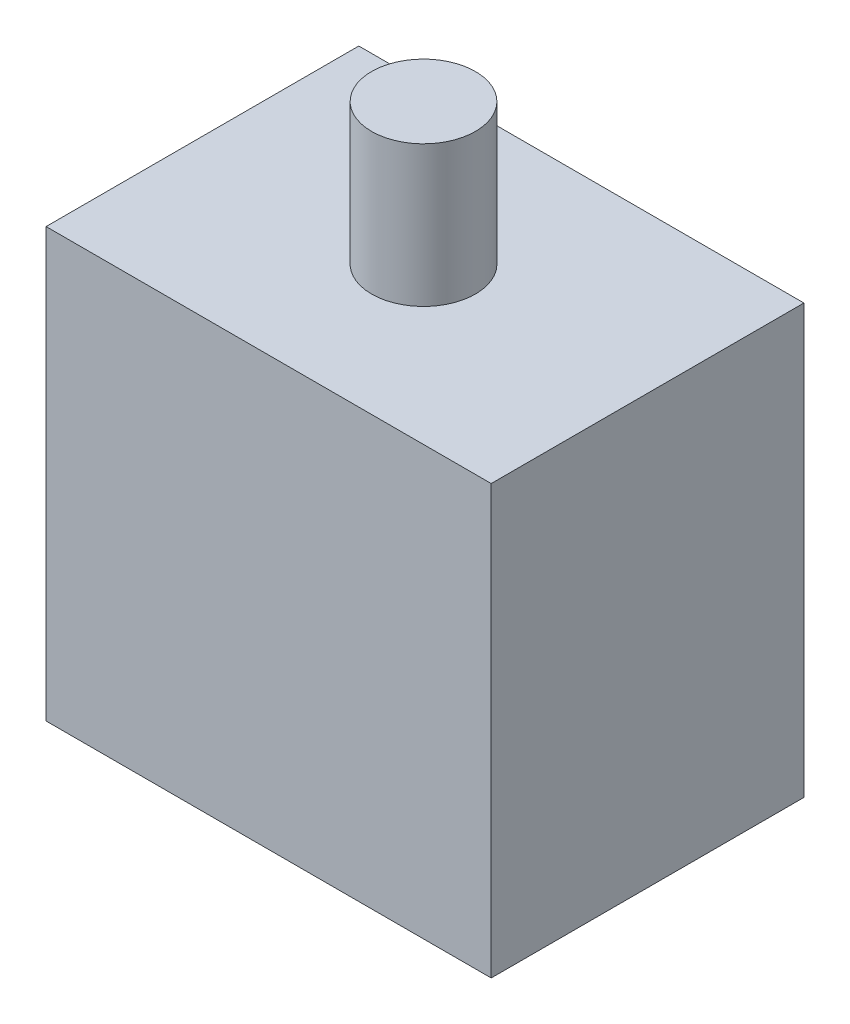
SolidWorks part; units mm, degrees
ref_plane "Front Plane" through (0, 0, 0) normal (0, 0, 1) x (1, 0, 0)
ref_plane "Top Plane" through (0, 0, 0) normal (0, 1, 0) x (1, 0, 0)
ref_plane "Right Plane" through (0, 0, 0) normal (1, 0, 0) x (0, 0, -1)
sketch "Sketch1" plane through (0, 0, 0) normal (0, 1, 0) x (1, 0, 0)
  line L1 (0, 0) -> (-80.264, 0)
  line L2 (0, 0) -> (0, 56.388)
  line L3 (0, 56.388) -> (-80.264, 56.388)
  line L4 (-80.264, 0) -> (-80.264, 56.388)
  dimension "D1" = 56.388
  dimension "D2" = 80.264
extrude "Boss-Extrude1" add sketch "Sketch1" along normal blind 77.216
sketch "Sketch2" plane through (0, 77.216, 0) normal (0, 1, 0) x (1, 0, 0)
  circle A0 centre (-40.3692, 28.1644) radius 9.3614
extrude "Boss-Extrude2" add sketch "Sketch2" along normal blind 25.4
